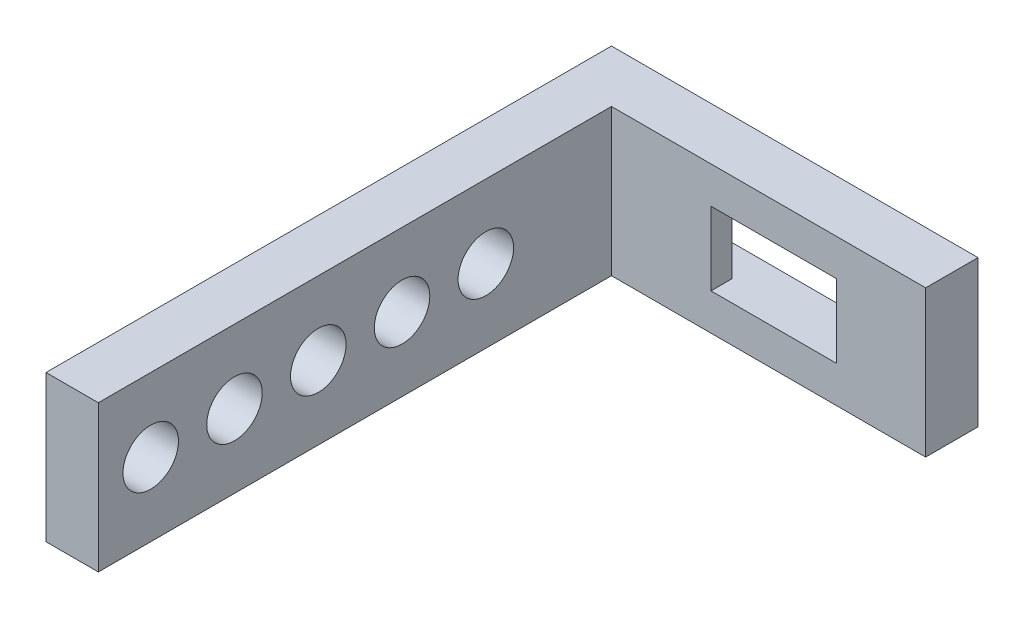
SolidWorks part; units mm, degrees
ref_plane "Front Plane" through (0, 0, 0) normal (0, 0, 1) x (1, 0, 0)
ref_plane "Top Plane" through (0, 0, 0) normal (0, 1, 0) x (1, 0, 0)
ref_plane "Right Plane" through (0, 0, 0) normal (1, 0, 0) x (0, 0, -1)
sketch "Sketch1" plane through (0, 0, 0) normal (0, 1, 0) x (1, 0, 0)
  line L2 (6.5891, 0) -> (10, 0)
  line L8 (0, 9) -> (11.5891, 9)
  line L10 (11.5891, 9) -> (40, 9)
  line L11 (40, 9) -> (40, 4)
  line L13 (6.5891, 0) -> (0, 0)
  line L15 (0, 0) -> (0, 9)
  line L17 (0, 0) -> (37.5449, 0) construction
  line L18 (10, 0) -> (10, 4)
  line L19 (10, 4) -> (40, 4)
  line L20 (25, 4) -> (25, 9) construction
  dimension "D2" = 25
  dimension "D4" = 30
  dimension "D9" = 5
  dimension "D10" = 4
extrude "Boss-Extrude1" add sketch "Sketch1" along normal blind 14
sketch "Sketch2" plane through (0, 0, -4) normal (0, 0, 1) x (1, 0, 0)
  line L0 (40, 7) -> (10, 7) construction
  line L1 (37.5, 3.5) -> (12.5, 3.5)
  line L2 (37.5, 3.5) -> (37.5, 10.5)
  line L3 (37.5, 10.5) -> (12.5, 10.5)
  line L4 (12.5, 3.5) -> (12.5, 10.5)
  line L6 (40, 14) -> (40, 0) construction
  line L7 (25, 3.5) -> (25, 10.5) construction
  line L8 (10, 14) -> (10, 0) construction
  line L11 (37.5, 7) -> (12.5, 7) construction
  line L14 (25, 14) -> (25, 0) construction
  line L15 (10, 14) -> (40, 14) construction
  line L16 (10, 0) -> (40, 0) construction
  dimension "D1" = 25
  dimension "D2" = 7
extrude "Cut-Extrude3" [suppressed] cut sketch "Sketch2" against normal blind 3
sketch "Sketch10" [suppressed] plane through (0, 0, -7) normal (0, 0, 1) x (1, 0, 0)
  line L0 (25, 10.5) -> (25, 3.5) construction
  line L1 (34, 9.5) -> (16, 9.5)
  line L2 (34, 9.5) -> (34, 4.5)
  line L3 (34, 4.5) -> (16, 4.5)
  line L4 (16, 9.5) -> (16, 4.5)
  line L5 (34, 9.5) -> (16, 4.5) construction
  line L6 (34, 4.5) -> (16, 9.5) construction
  line L7 (37.5, 10.5) -> (12.5, 10.5) construction
  line L8 (12.5, 3.5) -> (37.5, 3.5) construction
  line L9 (12.5, 7) -> (37.5, 7) construction
  line L10 (12.5, 10.5) -> (12.5, 3.5) construction
  line L11 (37.5, 3.5) -> (37.5, 10.5) construction
  point P0 (25, 7)
  point P11 (25, 9.5)
  point P18 (16, 7)
  dimension "D1" = 18
  dimension "D2" = 5
extrude "Cut-Extrude4" [suppressed] cut sketch "Sketch10" against normal through all
sketch "Sketch11" plane through (0, 0, 0) normal (-1, 0, 0) x (0, 0, 1)
  line L7 (-9, 14) -> (0, 14) construction
  line L12 (-5, 14) -> (-5, 24)
  line L18 (0, 14) -> (0, 15)
  line L20 (-5, 14) -> (0, 14)
  line L23 (-5, 24) -> (-2.8009, 24)
  line L24 (-2.8009, 24) -> (-2.8009, 15)
  line L25 (-2.8009, 15) -> (0, 15)
  dimension "D1" = 9
  dimension "D2" = 5
  dimension "D3" = 10
extrude "Boss-Extrude8" [suppressed] add sketch "Sketch11" against normal blind 3
sketch "Sketch12" [suppressed] plane through (3, 0, 0) normal (1, 0, 0) x (0, 0, -1)
  line L0 (2.8009, 15) -> (2.8009, 24) construction
  line L1 (8.4206, 15) -> (2.8009, 15) construction
  circle A0 centre (5.3009, 17.5) radius 2.5
  dimension "D1" = 5
extrude "Boss-Extrude9" [suppressed] add sketch "Sketch12" along normal blind 9
ref_plane "Plane1" through (10, 0, 0) normal (-1, 0, 0) x (0, 0, 1)
sketch "Sketch14" [suppressed] plane through (0, 0, -17.4206) normal (0, 0, -1) x (-1, 0, 0)
  line L0 (-59, 0) -> (0, 0) construction
  line L1 (-10, 0) -> (-3, 0)
  line L2 (-10, 0) -> (-10, 12)
  line L3 (-10, 12) -> (-3, 12)
  line L4 (-3, 0) -> (-3, 12)
  line L5 (-3, 24) -> (-3, 14) construction
  dimension "D1" = 12
  dimension "D2" = 7
sketch "Sketch15" [suppressed] plane through (0, 0, 0) normal (-1, 0, 0) x (0, 0, 1)
  line L1 (-8.1108, 24) -> (-8.1108, 15.2416) construction
  line L2 (-2.8009, 24) -> (-13.4206, 24) construction
  line L3 (-2.8009, 19.5) -> (-12.1862, 19.5) construction
  line L4 (-2.8009, 15) -> (-2.8009, 24) construction
  circle A0 centre (-8.1108, 19.5) radius 2.5
  dimension "D1" = 5
extrude "Cut-Extrude8" [suppressed] cut sketch "Sketch15" against normal through all
sketch "Sketch16" [suppressed] plane through (0, 0, -17.4206) normal (0, 0, -1) x (-1, 0, 0)
  line L0 (-59, 0) -> (0, 0) construction
  line L1 (-15, 11) -> (-3, 11)
  line L2 (-15, 11) -> (-15, 0)
  line L3 (-15, 0) -> (-3, 0)
  line L4 (-3, 11) -> (-3, 0)
  line L5 (-3, 24) -> (-3, 14) construction
  dimension "D1" = 12
  dimension "D2" = 11
extrude "Cut-Extrude9" [suppressed] cut sketch "Sketch16" against normal blind 9
sketch "Sketch19" [suppressed] plane through (0, 0, -17.4206) normal (0, 0, -1) x (-1, 0, 0)
  line L0 (-59, 0) -> (0, 0) construction
  line L1 (-13.7627, 0) -> (-3, 0)
  line L2 (-13.7627, 0) -> (-13.7627, 11.672)
  line L3 (-13.7627, 11.672) -> (-3, 11.672)
  line L4 (-3, 0) -> (-3, 11.672)
  line L5 (-3, 24) -> (-3, 14) construction
extrude "Cut-Extrude12" [suppressed] cut sketch "Sketch19" against normal blind 7
sketch "Sketch20" plane through (0, 0, 0) normal (-1, 0, 0) x (0, 0, 1)
  line L0 (-4, 14) -> (-4, 0) construction
  line L1 (0, 0) -> (45, 0)
  line L2 (0, 0) -> (0, 14)
  line L3 (0, 14) -> (45, 14)
  line L4 (45, 0) -> (45, 14)
  dimension "D1" = 49
extrude "Boss-Extrude10" add sketch "Sketch20" against normal blind 5
sketch "Sketch21" plane through (0, 0, 0) normal (-1, 0, 0) x (0, 0, 1)
  line L0 (-9, 14) -> (-9, 0) construction
  line L1 (-9, 7) -> (45, 7) construction
  line L2 (45, 0) -> (45, 14) construction
  circle A0 centre (0, 7) radius 2.65
  circle A3 centre (8, 7) radius 2.65
  circle A4 centre (16, 7) radius 2.65
  circle A5 centre (24, 7) radius 2.65
  circle A6 centre (32, 7) radius 2.65
  circle A7 centre (40, 7) radius 2.65
  dimension "D1" = 5.3
  dimension "D2" = 5
  dimension "D3" = 4
  dimension "D4" = 3
extrude "Cut-Extrude13" cut sketch "Sketch21" against normal up to surface (5 mm away) contours A0 | A3 | A4 | A5 | A6 | A7 up to face at (5, 7, 22.5)
sketch "Sketch22" plane through (0, 14, 0) normal (0, 1, 0) x (1, 0, 0)
  line L0 (10, 7.7) -> (10, -7.7) construction
  line L1 (5, 0) -> (10, 0)
  line L2 (5, 0) -> (5, 4)
  line L3 (5, 4) -> (10, 4)
  line L4 (10, 0) -> (10, 4)
  line L5 (10, 4) -> (40, 4) construction
extrude "Cut-Extrude14" cut sketch "Sketch22" against normal through all
sketch "Sketch23" plane through (0, 0, 0) normal (-1, 0, 0) x (0, 0, 1)
  circle A0 centre (0, 7) radius 2.65
extrude "Boss-Extrude11" add sketch "Sketch23" against normal up to surface (5 mm away) up to face at (5, 7, -2.65)
sketch "Sketch24" plane through (0, 0, -9) normal (0, 0, -1) x (-1, 0, 0)
  line L0 (0, 7) -> (-40, 7) construction
  line L1 (-8, 10.5) -> (-33, 10.5)
  line L2 (-8, 10.5) -> (-8, 3.5)
  line L3 (-8, 3.5) -> (-33, 3.5)
  line L4 (-33, 10.5) -> (-33, 3.5)
  line L5 (0, 14) -> (0, 0) construction
  line L6 (-40, 14) -> (-40, 0) construction
  point P10 (-8, 7)
  dimension "D1" = 25
  dimension "D2" = 7
  dimension "D3" = 7
extrude "Cut-Extrude15" cut sketch "Sketch24" against normal blind 3
sketch "Sketch25" plane through (0, 0, -6) normal (0, 0, -1) x (-1, 0, 0)
  line L0 (-20.5, 3.5) -> (-20.5, 10.5) construction
  line L1 (-14.5, 10.5) -> (-26.5, 10.5)
  line L2 (-14.5, 10.5) -> (-14.5, 3.5)
  line L3 (-14.5, 3.5) -> (-26.5, 3.5)
  line L4 (-26.5, 10.5) -> (-26.5, 3.5)
  line L5 (-14.5, 10.5) -> (-26.5, 3.5) construction
  line L6 (-14.5, 3.5) -> (-26.5, 10.5) construction
  line L7 (-33, 3.5) -> (-8, 3.5) construction
  line L8 (-8, 10.5) -> (-33, 10.5) construction
  line L9 (-33, 10.5) -> (-33, 3.5) construction
  point P0 (-20.5, 7)
  point P14 (-33, 7)
  point P15 (-26.5, 7)
  dimension "D1" = 12
  dimension "D2" = 7
extrude "Cut-Extrude16" cut sketch "Sketch25" against normal up to next
sketch "Sketch26" plane through (0, 0, -9) normal (0, 0, -1) x (-1, 0, 0)
  line L0 (-40, 14) -> (0, 14) construction
  line L1 (-40, 0) -> (-35, 0)
  line L2 (-40, 0) -> (-40, 14)
  line L3 (-40, 14) -> (-35, 14)
  line L4 (-35, 0) -> (-35, 14)
  line L5 (-33, 10.5) -> (-33, 3.5) construction
  dimension "D1" = 2
extrude "Cut-Extrude17" cut sketch "Sketch26" against normal up to next
